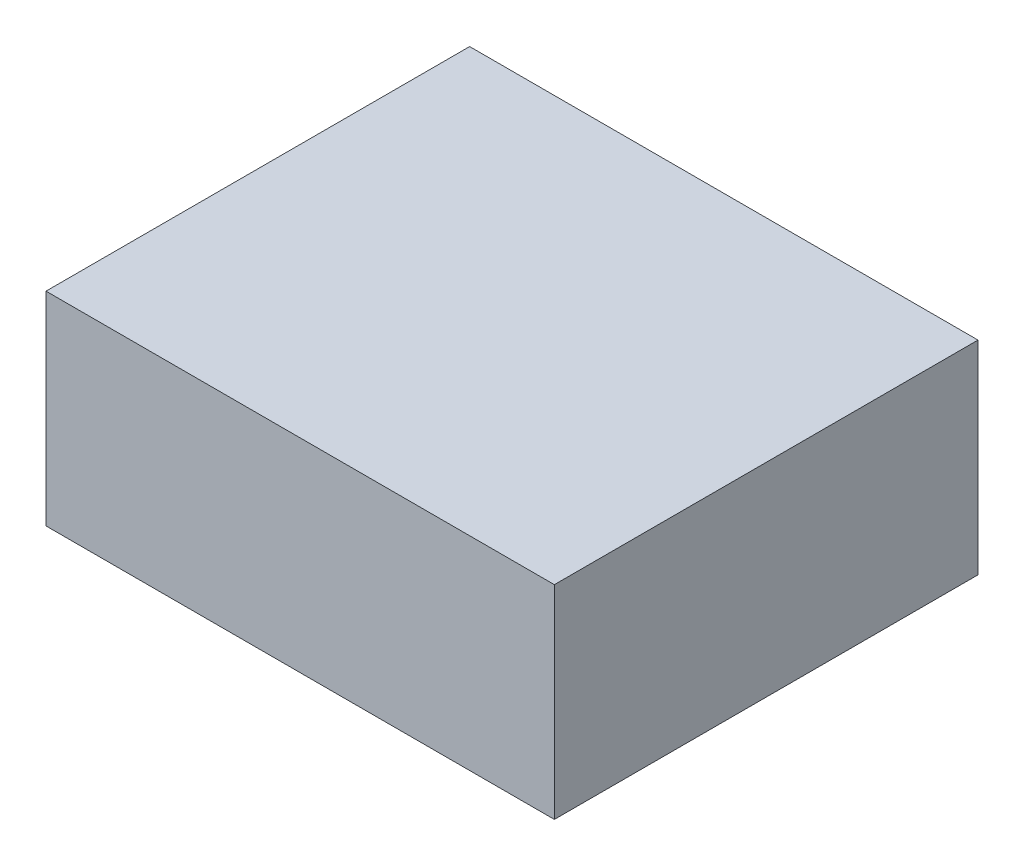
SolidWorks part; units mm, degrees
material "7075-T6 (SN)"
ref_plane "Front Plane" through (0, 0, 0) normal (0, 0, 1) x (1, 0, 0)
ref_plane "Top Plane" through (0, 0, 0) normal (0, 1, 0) x (1, 0, 0)
ref_plane "Right Plane" through (0, 0, 0) normal (1, 0, 0) x (0, 0, -1)
sketch "Sketch1" plane through (0, 0, 0) normal (0, 1, 0) x (1, 0, 0)
  line L7 (-150, 125) -> (150, 125)
  line L8 (-150, 125) -> (-150, -125)
  line L9 (-150, -125) -> (150, -125)
  line L10 (150, 125) -> (150, -125)
  line L11 (-150, 125) -> (150, -125) construction
  line L12 (-150, -125) -> (150, 125) construction
  point P0 (0, 0)
  point P1 (14.3633, -2.4482)
  point P6 (0, 0)
  dimension "D1" = 300
  dimension "D2" = 250
extrude "Boss-Extrude1" add sketch "Sketch1" along normal blind 1.25
sketch "Sketch5" plane through (0, 0, 0) normal (0, 1, 0) x (1, 0, 0)
  line L1 (-148.75, 123.75) -> (148.75, 123.75)
  line L2 (-148.75, 123.75) -> (-148.75, -123.75)
  line L3 (-148.75, -123.75) -> (148.75, -123.75)
  line L4 (150, -125) -> (150, 125)
  line L5 (150, 125) -> (-150, 125)
  line L6 (-150, 125) -> (-150, -125)
  line L7 (-150, -125) -> (150, -125)
  line L8 (150, -125) -> (150, 125)
  line L9 (150, 125) -> (-150, 125)
  line L10 (-150, 125) -> (-150, -125)
  line L11 (-150, -125) -> (150, -125)
  line L12 (148.75, 123.75) -> (148.75, -123.75)
  line L13 (-148.75, 123.75) -> (148.75, -123.75) construction
  line L14 (-148.75, -123.75) -> (148.75, 123.75) construction
  point P2 (0, 0)
  dimension "D2" = 1.25
  dimension "D3" = 1.25
  dimension "D1" = 0
extrude "Boss-Extrude2" add sketch "Sketch5" along normal blind 120
sketch "Sketch6" plane through (0, 120, 0) normal (0, 1, 0) x (1, 0, 0)
  line L0 (-150, -125) -> (150, -125) construction
  line L1 (150, -125) -> (150, 125) construction
  line L2 (150, 125) -> (-150, 125) construction
  line L3 (-150, 125) -> (-150, -125) construction
  line L4 (-150, -125) -> (150, -125)
  line L5 (150, -125) -> (150, 125)
  line L6 (150, 125) -> (-150, 125)
  line L7 (-150, 125) -> (-150, -125)
extrude "Boss-Extrude3" add sketch "Sketch6" against normal blind 1.25
